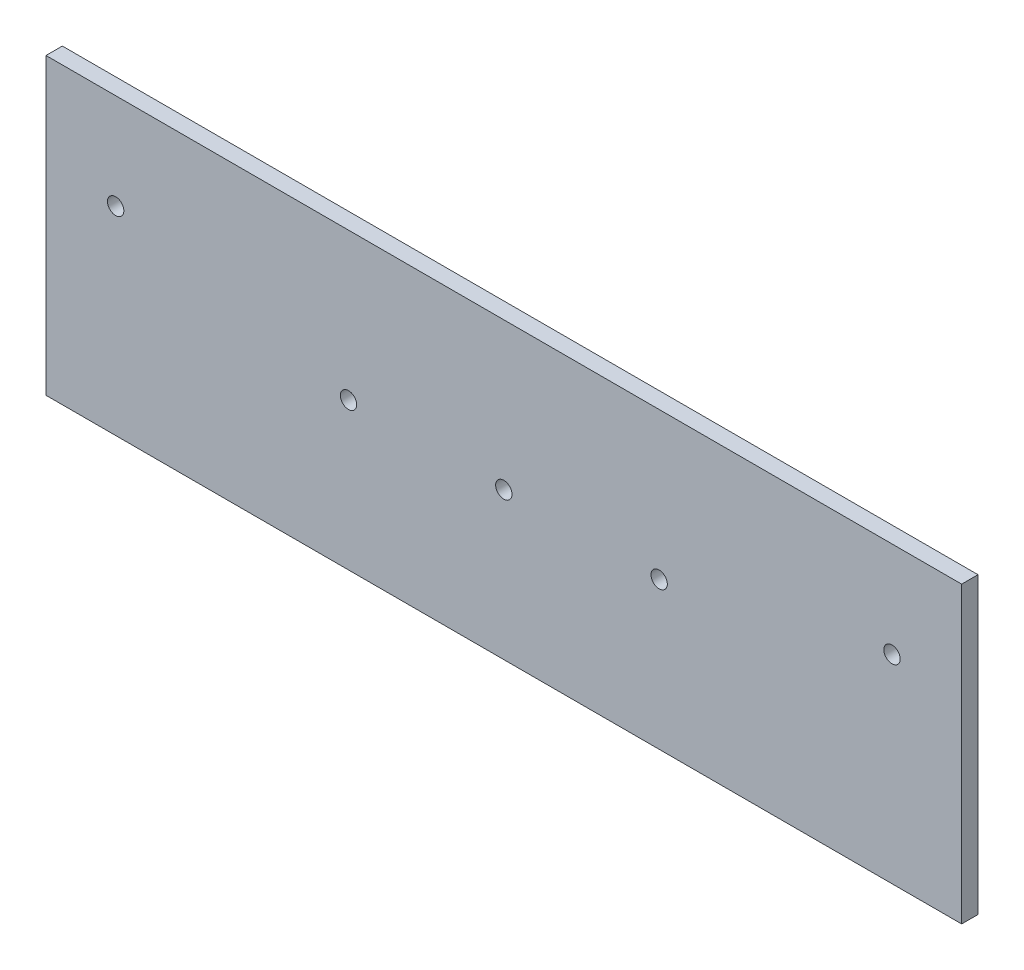
SolidWorks part; units mm, degrees
ref_plane "Front Plane" through (0, 0, 0) normal (0, 0, 1) x (1, 0, 0)
ref_plane "Top Plane" through (0, 0, 0) normal (0, 1, 0) x (1, 0, 0)
ref_plane "Right Plane" through (0, 0, 0) normal (1, 0, 0) x (0, 0, -1)
sketch "Sketch1" plane through (0, 0, 0) normal (0, 0, 1) x (1, 0, 0)
  line L1 (-177.8, -57.15) -> (177.8, -57.15)
  line L2 (-177.8, -57.15) -> (-177.8, 57.15)
  line L3 (-177.8, 57.15) -> (177.8, 57.15)
  line L4 (177.8, -57.15) -> (177.8, 57.15)
  line L5 (-177.8, -57.15) -> (177.8, 57.15) construction
  line L6 (-177.8, 57.15) -> (177.8, -57.15) construction
  point P0 (0, 0)
  dimension "D1" = 355.6
  dimension "D2" = 114.3
extrude "Boss-Extrude1" add sketch "Sketch1" along normal blind 6.35
sketch "Sketch3" plane through (0, 0, 6.35) normal (0, 0, 1) x (1, 0, 0)
  line L0 (0, 92.3884) -> (0, -106.1191) construction
  line L1 (102.534, -107.8807) -> (162.859, -107.8807) construction
  line L2 (102.534, -107.8807) -> (102.534, -87.8807) construction
  line L3 (102.534, -87.8807) -> (12.11, -87.8807) construction
  line L4 (132.6965, -107.8807) -> (132.6965, -116.3437) construction
  line L5 (-60.325, 0) -> (0, 0) construction
  line L6 (-60.325, 0) -> (-60.325, 20) construction
  line L7 (-60.325, 20) -> (-150.749, 20) construction
  line L8 (-30.1625, 0) -> (-30.1625, -8.4631) construction
  circle A0 centre (102.534, -107.8807) radius 3.175 construction
  circle A1 centre (162.859, -107.8807) radius 3.175 construction
  circle A2 centre (12.11, -87.8807) radius 3.175 construction
  circle A12 centre (-60.325, 0) radius 3.175
  circle A13 centre (0, 0) radius 3.175
  circle A14 centre (-150.749, 20) radius 3.175
  dimension "D2" = 6.35
  dimension "D5" = 6.35
  dimension "D7" = 6.35
  dimension "D10" = 6.35
  dimension "D1" = 60.325
  dimension "D3" = 20
  dimension "D4" = 90.424
  dimension "D6" = 60.325
  dimension "D8" = 20
  dimension "D9" = 90.424
extrude "Cut-Extrude1" cut sketch "Sketch3" against normal up to surface (6.35 mm away) up to face at (0, 0, 0)
ref_plane "Plane1" through (0, 0, 0) normal (1, 0, 0) x (0, 0, -1)
mirror "Mirror3" about plane through (0, 0, 0) normal (1, 0, 0) of "Cut-Extrude1"
